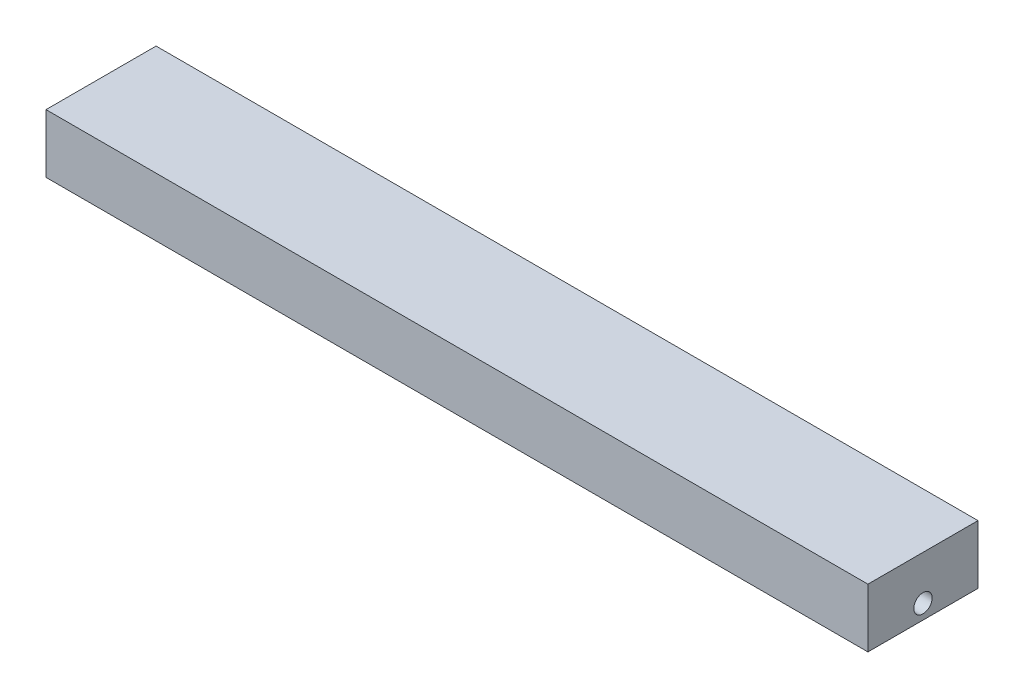
SolidWorks part; units mm, degrees
ref_plane "Front" through (0, 0, 0) normal (0, 0, 1) x (1, 0, 0)
ref_plane "Top" through (0, 0, 0) normal (0, 1, 0) x (1, 0, 0)
ref_plane "Right" through (0, 0, 0) normal (1, 0, 0) x (0, 0, -1)
sketch "Skizze1" plane through (0, 0, 0) normal (0, 1, 0) x (1, 0, 0)
  line L1 (-56, -7.5) -> (56, -7.5)
  line L2 (-56, -7.5) -> (-56, 7.5)
  line L3 (-56, 7.5) -> (56, 7.5)
  line L4 (56, -7.5) -> (56, 7.5)
  line L5 (-56, -7.5) -> (56, 7.5) construction
  line L6 (-56, 7.5) -> (56, -7.5) construction
  point P0 (0, 0)
  dimension "D1" = 112
  dimension "D2" = 15
extrude "Aufsatz-Linear austragen1" add sketch "Skizze1" along normal blind 8
sketch "Skizze2" plane through (56, 0, 0) normal (1, 0, 0) x (0, 0, -1)
  line L0 (0, 2.5841) -> (0, -49997.4159) construction
  line L1 (0, 2) -> (50000, 2) construction
  line L2 (-7.5, 0) -> (7.5, 0) construction
  circle A0 centre (0, 2) radius 1.25
  point P8 (0, 0)
  dimension "D1" = 2
  dimension "D2" = 2.5
extrude "Schnitt-Linear austragen1" cut sketch "Skizze2" against normal through all
